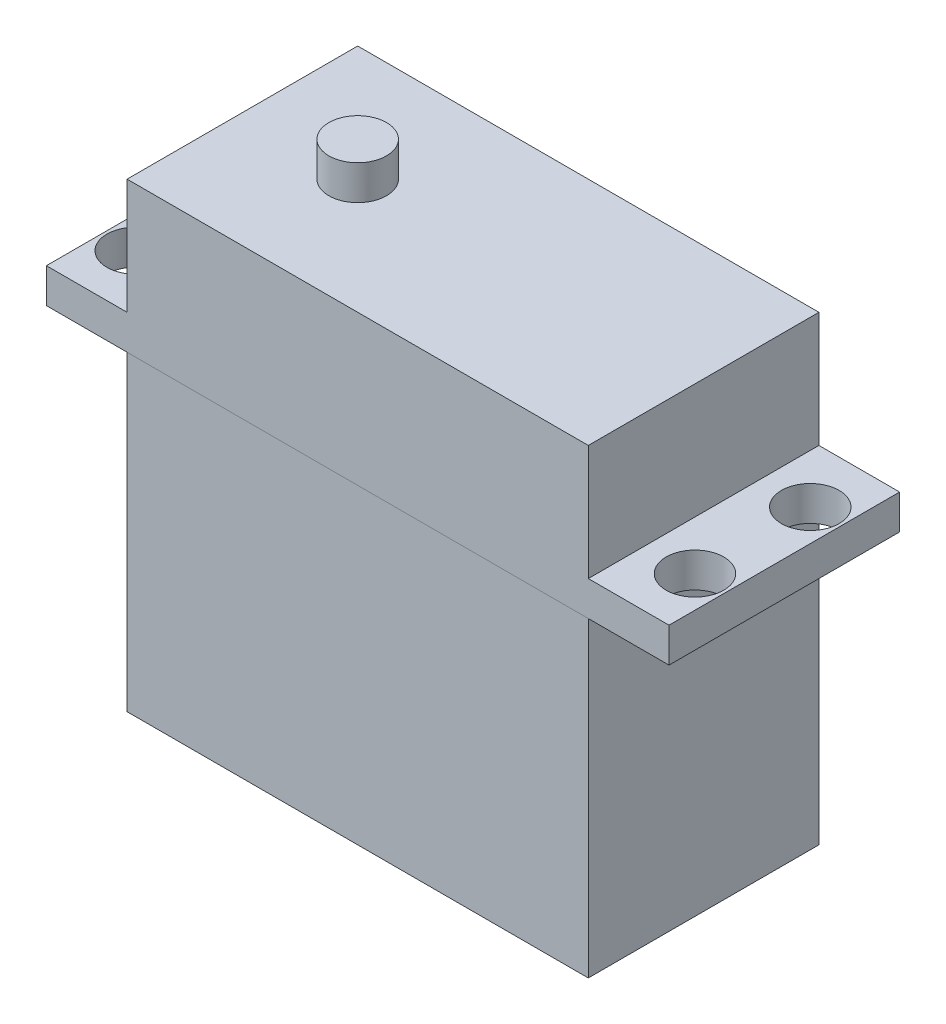
SolidWorks part; units mm, degrees
ref_plane "Front Plane" through (0, 0, 0) normal (0, 0, 1) x (1, 0, 0)
ref_plane "Top Plane" through (0, 0, 0) normal (0, 1, 0) x (1, 0, 0)
ref_plane "Right Plane" through (0, 0, 0) normal (1, 0, 0) x (0, 0, -1)
sketch "Sketch1" plane through (0, 0, 0) normal (0, 1, 0) x (1, 0, 0)
  line L1 (-20, -10) -> (20, -10)
  line L2 (-20, -10) -> (-20, 10)
  line L3 (-20, 10) -> (20, 10)
  line L4 (20, -10) -> (20, 10)
  line L5 (-20, -10) -> (20, 10) construction
  line L6 (-20, 10) -> (20, -10) construction
  point P0 (0, 0)
  dimension "D1" = 20
  dimension "D2" = 40
extrude "Boss-Extrude1" add sketch "Sketch1" along normal blind 27
sketch "Sketch2" plane through (0, 27, 0) normal (0, 1, 0) x (1, 0, 0)
  line L1 (-27, -10) -> (27, -10)
  line L2 (-27, -10) -> (-27, 10)
  line L3 (-27, 10) -> (27, 10)
  line L4 (27, -10) -> (27, 10)
  line L5 (-27, -10) -> (27, 10) construction
  line L6 (-27, 10) -> (27, -10) construction
  circle A0 centre (-24.25, 5) radius 2.5
  circle A1 centre (-24.25, -5) radius 2.5
  circle A2 centre (24.25, -5) radius 2.5
  circle A3 centre (24.25, 5) radius 2.5
  point P0 (0, 0)
  dimension "D3" = 5
  dimension "D7" = 2.75
  dimension "D9" = 2.75
  dimension "D10" = 2.75
  dimension "D11" = 2.75
  dimension "D1" = 54
  dimension "D2" = 20
  dimension "D4" = 10
  dimension "D5" = 10
  dimension "D6" = 5
  dimension "D8" = 5
extrude "Boss-Extrude4" add sketch "Sketch2" along normal blind 3 separate body
sketch "Sketch3" plane through (0, 30, 0) normal (0, 1, 0) x (1, 0, 0)
  line L0 (27, 10) -> (-27, 10) construction
  line L1 (-20, -10) -> (20, -10)
  line L2 (-20, -10) -> (-20, 10)
  line L3 (-20, 10) -> (20, 10)
  line L4 (20, -10) -> (20, 10)
  line L5 (-20, -10) -> (20, 10) construction
  line L6 (-20, 10) -> (20, -10) construction
  point P0 (0, 0)
  dimension "D1" = 40
extrude "Boss-Extrude5" add sketch "Sketch3" along normal blind 10
ref_plane "Plane1" through (20, 27, -10) normal (0, -1, 0) x (-1, 0, 0)
sketch "Sketch5" plane through (0, 40, 0) normal (0, 1, 0) x (1, 0, 0)
  line L0 (-20, -10) -> (20, -10) construction
  circle A0 centre (-10, 0) radius 2.5
  dimension "D1" = 5
  dimension "D2" = 10
  dimension "D3" = 10
extrude "Boss-Extrude6" add sketch "Sketch5" along normal blind 3 contours A0
